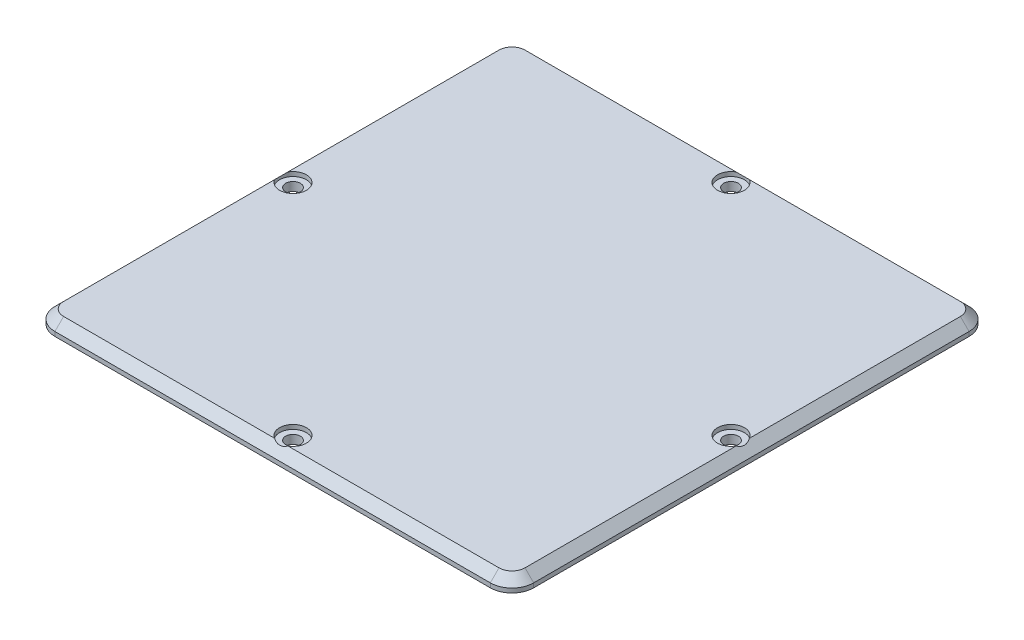
SolidWorks part; units mm, degrees
ref_plane "Front Plane" through (0, 0, 0) normal (0, 0, 1) x (1, 0, 0)
ref_plane "Top Plane" through (0, 0, 0) normal (0, 1, 0) x (1, 0, 0)
ref_plane "Right Plane" through (0, 0, 0) normal (1, 0, 0) x (0, 0, -1)
sketch "Sketch1" plane through (0, 0, 0) normal (0, 1, 0) x (1, 0, 0)
  line L1 (0, 0) -> (121, 0)
  line L2 (0, 0) -> (0, 121)
  line L3 (0, 121) -> (121, 121)
  line L4 (121, 0) -> (121, 121)
  line L5 (10.3, 5.3) -> (110.7, 5.3)
  line L6 (5.3, 10.3) -> (5.3, 110.7)
  line L7 (10.3, 115.7) -> (110.7, 115.7)
  line L8 (115.7, 10.3) -> (115.7, 110.7)
  arc A0 (10.3, 5.3) -> (5.3, 10.3) centre (10.3, 10.3) cw
  arc A1 (110.7, 5.3) -> (115.7, 10.3) centre (110.7, 10.3) ccw
  arc A2 (110.7, 115.7) -> (115.7, 110.7) centre (110.7, 110.7) cw
  arc A3 (5.3, 110.7) -> (10.3, 115.7) centre (10.3, 110.7) cw
  dimension "D7" = 5
  dimension "D1" = 121
  dimension "D2" = 121
  dimension "D3" = 5.3
  dimension "D4" = 5.3
  dimension "D5" = 5.3
  dimension "D6" = 5.3
extrude "Boss-Extrude1" add sketch "Sketch1" along normal blind 3 contours A3 L6 A0 L5 A1 L8 A2 L7
chamfer "Chamfer1" distance 2 angle 45 8 edges at (60.5, 3, -5.3) (115.7, 3, -60.5) (5.3, 3, -60.5) (6.7645, 3, -6.7645) (114.2355, 3, -6.7645) (6.7645, 3, -114.2355) (114.2355, 3, -114.2355) (60.5, 3, -115.7)
hole_wizard "CBORE for M3 Cross Recess Pan Head Screw1" positions "Sketch3" profile "Sketch4" counterbore size "M3" standard "IS"
sketch "Sketch3" plane through (0, 3, 0) normal (0, 1, 0) x (1, 0, 0)
  line L0 (10.3, 7.3) -> (110.7, 7.3) construction
  line L1 (113.7, 10.3) -> (113.7, 110.7) construction
  line L2 (110.7, 5.3) -> (10.3, 5.3) construction
  line L3 (115.7, 110.7) -> (115.7, 10.3) construction
  point P0 (60.5, 111)
  point P1 (10, 60.5)
  point P3 (60.5, 10)
  point P5 (111, 60.5)
  point P10 (60.5, 7.3)
  point P13 (113.7, 60.5)
  dimension "D1" = 101
  dimension "D2" = 101
  dimension "D3" = 0
  dimension "D4" = 0
  dimension "D5" = 4.7
  dimension "D6" = 4.7
sketch "Sketch4" plane through (60.5, 3, -111) normal (1, 0, 0) x (0, 0, 1)
  line L0 (0, 0) -> (0, 6.0215)
  line L1 (0, 6.0215) -> (1.7, 5)
  line L2 (1.7, 5) -> (1.7, 1)
  line L3 (1.7, 1) -> (3.1, 1)
  line L4 (3.1, 1) -> (3.1, 0)
  line L5 (3.1, 0) -> (0, 0)
  line L10 (0, 6.0215) -> (-1.7, 5) construction
  line L11 (0, -6.35) -> (0, 107.95) construction
  dimension "Hole Dia." = 3.4
  dimension "Hole Depth" = 5
  dimension "C'Bore Dia." = 6.2
  dimension "C'Bore Depth" = 1
  dimension "Drill Angle" = 118
sketch "Sketch10" plane through (0, 0, 0) normal (0, -1, 0) x (1, 0, 0)
  line L0 (84.25, -84.2642) -> (84.25, -36.7642)
  line L1 (84.25, -36.7642) -> (36.75, -36.7642)
  line L2 (10.3, -5.3) -> (110.7, -5.3) construction
  circle A0 centre (36.75, -36.7642) radius 5
  circle A1 centre (36.75, -84.2642) radius 5
  circle A2 centre (84.25, -84.2642) radius 5
  circle A3 centre (84.25, -36.7642) radius 5
  point P8 (60.5, -36.7642)
  point P11 (60.5, -5.3)
  dimension "D1" = 10
  dimension "D2" = 10
  dimension "D3" = 10
  dimension "D4" = 10
  dimension "D5" = 47.5
  dimension "D6" = 47.5
  dimension "D7" = 47.5
  dimension "D8" = 47.5
  dimension "D9" = 0
extrude "Boss-Extrude4" add sketch "Sketch10" along normal blind 11
sketch "Sketch11" plane through (0, 0, 0) normal (1, 0, 0) x (0, 0, -1)
  line L0 (31.7642, -11) -> (31.7642, -6)
  line L1 (31.7642, 0) -> (31.7642, -11) construction
  line L2 (31.7642, -6) -> (89.2642, -11)
  line L3 (89.2642, -11) -> (31.7642, -11)
  dimension "D1" = 5
extrude "Cut-Extrude4" cut sketch "Sketch11" along normal up to surface (115.7 mm away) up to face at (115.7, 0.5, -60.5)
sketch "Sketch12" plane through (0, -3.2136, 0.2794) normal (0, -0.9962, 0.0866) x (1, 0, 0)
  circle A0 centre (84.25, -84.8626) radius 2.2
  circle A1 centre (36.75, -84.8626) radius 2.2
  circle A2 centre (36.75, -37.1834) radius 2.2
  circle A3 centre (84.25, -37.1834) radius 2.2
extrude "Cut-Extrude5" cut sketch "Sketch12" against normal blind 6
